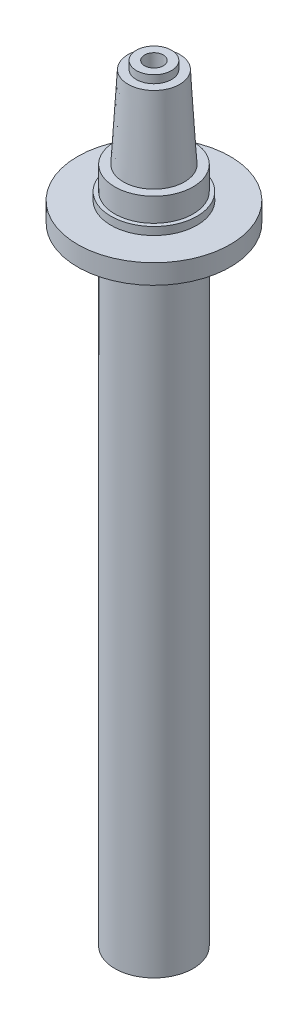
SolidWorks part; units mm, degrees
ref_plane "Front Plane" through (0, 0, 0) normal (0, 0, 1) x (1, 0, 0)
ref_plane "Top Plane" through (0, 0, 0) normal (0, 1, 0) x (1, 0, 0)
ref_plane "Right Plane" through (0, 0, 0) normal (1, 0, 0) x (0, 0, -1)
sketch "Sketch1" plane through (0, 0, 0) normal (0, 0, 1) x (1, 0, 0)
  line L0 (0, 0) -> (5, 0)
  line L1 (5, 0) -> (5, 80)
  line L2 (5, 80) -> (9.75, 80)
  line L3 (9.75, 80) -> (9.75, 82.5)
  line L4 (9.75, 82.5) -> (5, 82.5)
  line L5 (5, 82.5) -> (5, 86.5)
  line L6 (5, 86.5) -> (3.9, 86.5)
  line L7 (3.9, 86.5) -> (3.3, 97)
  line L8 (3.3, 97) -> (2.25, 97)
  line L9 (2.25, 97) -> (2.25, 98)
  line L10 (2.25, 98) -> (1.2, 98)
  line L11 (1.2, 98) -> (1.2, 92)
  line L12 (1.2, 92) -> (0, 92)
  line L13 (0, 92) -> (0, 0)
  dimension "D1" = 5
  dimension "D2" = 80
  dimension "D3" = 9.75
  dimension "D4" = 2.5
  dimension "D5" = 98
  dimension "D6" = 6
  dimension "D7" = 1.2
  dimension "D8" = 1
  dimension "D9" = 2.25
  dimension "D10" = 3.3
  dimension "D11" = 4
  dimension "D12" = 3.9
revolve "Revolve1" add sketch "Sketch1" angle 360 about L13
sketch "Sketch2" plane through (0, 82.5, 0) normal (0, 1, 0) x (1, 0, 0)
  circle A0 centre (0, 0) radius 5.5
  dimension "D1" = 11
extrude "Boss-Extrude1" add sketch "Sketch2" along normal blind 1
